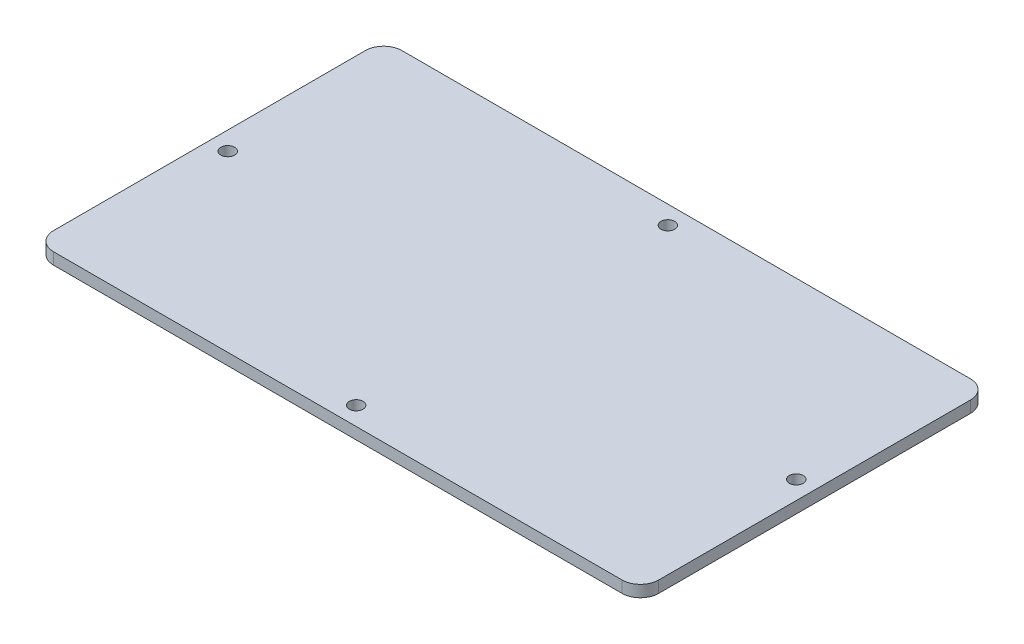
SolidWorks part; units mm, degrees
ref_plane "Front Plane" through (0, 0, 0) normal (0, 0, 1) x (1, 0, 0)
ref_plane "Top Plane" through (0, 0, 0) normal (0, 1, 0) x (1, 0, 0)
ref_plane "Right Plane" through (0, 0, 0) normal (1, 0, 0) x (0, 0, -1)
sketch "Sketch1" plane through (0, 0, 0) normal (0, 1, 0) x (1, 0, 0)
  line L0 (-165, 47.5) -> (0, 47.5) construction
  line L1 (-5, 0) -> (-160, 0)
  line L2 (0, 5) -> (0, 90)
  line L3 (-5, 95) -> (-160, 95)
  line L4 (-165, 5) -> (-165, 90)
  line L5 (-82.5, 95) -> (-82.5, 0) construction
  arc A0 (-160, 0) -> (-165, 5) centre (-160, 5) cw
  arc A1 (-5, 0) -> (0, 5) centre (-5, 5) ccw
  arc A2 (0, 90) -> (-5, 95) centre (-5, 90) ccw
  arc A3 (-160, 95) -> (-165, 90) centre (-160, 90) ccw
  circle A4 centre (-160, 47.5) radius 1.875
  circle A5 centre (-5, 47.5) radius 1.875
  circle A6 centre (-82.5, 90) radius 1.875
  circle A7 centre (-82.5, 5) radius 1.875
  point P9 (0, 0)
  dimension "D3" = 5
  dimension "D4" = 5
  dimension "D5" = 3.75
  dimension "D6" = 5
  dimension "D13" = 5
  dimension "D14" = 3.75
  dimension "D15" = 3.75
  dimension "D7" = 3.75
  dimension "D1" = 95
  dimension "D2" = 165
  dimension "D12" = 5
extrude "Boss-Extrude1" add sketch "Sketch1" along normal blind 3.175
